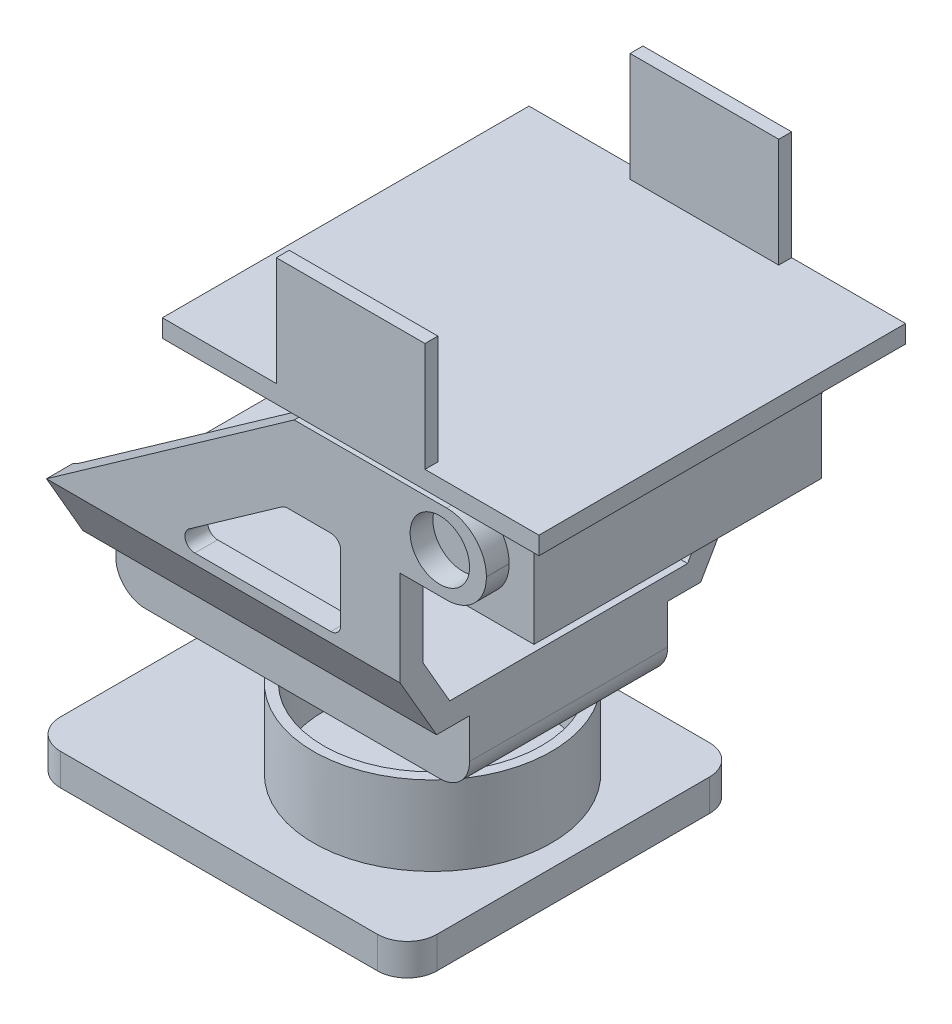
SolidWorks part; units mm, degrees
ref_plane "Alzado" through (0, 0, 0) normal (0, 0, 1) x (1, 0, 0)
ref_plane "Planta" through (0, 0, 0) normal (0, 1, 0) x (1, 0, 0)
ref_plane "Vista lateral" through (0, 0, 0) normal (1, 0, 0) x (0, 0, -1)
sketch "Croquis1" plane through (0, 0, 0) normal (0, 1, 0) x (1, 0, 0)
  line L1 (-16, -16.75) -> (16, -16.75)
  line L2 (-19, -13.75) -> (-19, 13.75)
  line L3 (-16, 16.75) -> (16, 16.75)
  line L4 (19, -13.75) -> (19, 13.75)
  line L5 (-19, -16.75) -> (19, 16.75) construction
  line L6 (-19, 16.75) -> (19, -16.75) construction
  arc A0 (-16, -16.75) -> (-19, -13.75) centre (-16, -13.75) cw
  arc A1 (16, -16.75) -> (19, -13.75) centre (16, -13.75) ccw
  arc A2 (16, 16.75) -> (19, 13.75) centre (16, 13.75) cw
  arc A3 (-19, 13.75) -> (-16, 16.75) centre (-16, 13.75) cw
  point P0 (0, 0)
  dimension "D3" = 3
  dimension "D1" = 38
  dimension "D2" = 33.5
extrude "Saliente-Extruir1" add sketch "Croquis1" along normal blind 3.2
sketch "Croquis2" plane through (0, 3.2, 0) normal (0, 1, 0) x (1, 0, 0)
  line L0 (4.8, 15.0241) -> (4.8, -18.394) construction
  line L1 (24.2913, 0) -> (-22.5361, 0) construction
  line L2 (19, -13.75) -> (19, 13.75) construction
  circle A0 centre (4.8, 0) radius 12
  circle A1 centre (4.8, 0) radius 11
  point P9 (0, 0)
  dimension "D2" = 24
  dimension "D1" = 14.2
  dimension "D3" = 1
extrude "Saliente-Extruir2" add sketch "Croquis2" along normal blind 8
sketch "Croquis3" plane through (0, 0, 0) normal (0, 0, 1) x (1, 0, 0)
  line L0 (4.8, 15.1383) -> (4.8, -3.1383) construction
  line L1 (16.8, 11.2) -> (-7.2, 11.2) construction
  line L2 (11.8, 13.2) -> (-10.42, 13.2)
  line L3 (11.8, 13.2) -> (11.8, 11.2)
  line L4 (11.8, 11.2) -> (-10.42, 11.2)
  line L5 (-10.42, 13.2) -> (-10.42, 11.2)
  dimension "D1" = 4.8
  dimension "D2" = 22.22
  dimension "D3" = 7
  dimension "D4" = 2
extrude "Saliente-Extruir3" add sketch "Croquis3" along normal mid plane 12
sketch "Croquis4" plane through (0, 0, 0) normal (0, 0, 1) x (1, 0, 0)
  line L0 (0.69, 13.2) -> (0.69, 23.3962) construction
  line L1 (11.8, 13.2) -> (-10.42, 13.2) construction
  line L3 (18.54, 20.2) -> (-17.16, 20.2)
  line L4 (18.54, 20.2) -> (18.54, 16.2)
  line L5 (15.54, 13.2) -> (-14.16, 13.2)
  line L6 (-17.16, 20.2) -> (-17.16, 16.2)
  arc A0 (18.54, 16.2) -> (15.54, 13.2) centre (15.54, 16.2) cw
  arc A1 (-17.16, 16.2) -> (-14.16, 13.2) centre (-14.16, 16.2) ccw
  point P8 (0.69, 23.3962)
  point P9 (-17.16, 21.2055)
  point P14 (-17.16, 13.2)
  dimension "D3" = 3
  dimension "D1" = 7
  dimension "D2" = 35.7
extrude "Saliente-Extruir4" add sketch "Croquis4" along normal mid plane 20
sketch "Croquis5" plane through (18.54, 0, 0) normal (1, 0, 0) x (0, 0, -1)
  line L0 (0, 29.5773) -> (0, 9.2688) construction
  line L1 (0, 22.5) -> (0, 20.2)
  line L2 (13.3279, 20.2) -> (-13.3279, 20.2)
  line L3 (-13.3279, 20.2) -> (-17, 26.5603)
  line L4 (-17, 26.5603) -> (-17, 44.2)
  line L5 (-17, 44.2) -> (-14.7, 44.2)
  line L6 (-14.7, 44.2) -> (-14.7, 27.1765)
  line L7 (-14.7, 27.1765) -> (-12, 22.5)
  line L8 (-12, 22.5) -> (12, 22.5)
  line L9 (-10, 20.2) -> (10, 20.2) construction
  line L10 (14.7, 27.1765) -> (12, 22.5)
  line L11 (14.7, 44.2) -> (14.7, 27.1765)
  line L12 (17, 44.2) -> (14.7, 44.2)
  line L13 (17, 26.5603) -> (17, 44.2)
  line L14 (13.3279, 20.2) -> (17, 26.5603)
  line M11 (10, 20.2) -> (-10, 20.2)
  dimension "D1" = 2.3
  dimension "D2" = 2.3
  dimension "D3" = 2.3
  dimension "D4" = 24
  dimension "D5" = 12
  dimension "D6" = 17
  dimension "D7" = 120
extrude "Saliente-Extruir5" add sketch "Croquis5" along direction (1, 0, 0) on the side against the normal up to vertex (35.7 mm away) contours L8 L7 L6 L5 L4 L3 L2 L1 M11 | L2 L14 L13 L12 L11 L10 L8 L1 M11
sketch "Croquis6" plane through (0, 0, 0) normal (0, 0, 1) x (1, 0, 0)
  line L0 (-17.16, 26.5603) -> (7.84, 44.2)
  line L1 (-17.16, 44.2) -> (18.54, 44.2) construction
  line L2 (7.84, 44.2) -> (-17.16, 44.2)
  line L3 (-17.16, 44.2) -> (-17.16, 26.5603)
  line L4 (-2.1838, 27.5603) -> (11.54, 27.5603)
  line L5 (12.54, 28.5603) -> (12.54, 35.1603)
  line L6 (6.5936, 35.9773) -> (-2.7603, 29.3773)
  line L7 (7.1701, 36.1603) -> (11.54, 36.1603)
  line L8 (-17.16, 26.5603) -> (18.54, 26.5603) construction
  line L9 (18.54, 26.5603) -> (18.54, 44.2) construction
  arc A0 (11.54, 27.5603) -> (12.54, 28.5603) centre (11.54, 28.5603) ccw
  arc A1 (-2.1838, 27.5603) -> (-2.7603, 29.3773) centre (-2.1838, 28.5603) cw
  arc A2 (7.1701, 36.1603) -> (6.5936, 35.9773) centre (7.1701, 35.1603) ccw
  arc A3 (11.54, 36.1603) -> (12.54, 35.1603) centre (11.54, 35.1603) cw
  point P17 (12.54, 27.5603)
  point P24 (12.54, 36.1603)
  dimension "D6" = 1
  dimension "D1" = 25
  dimension "D2" = 6
  dimension "D3" = 6
  dimension "D4" = 8.6
  dimension "D5" = 1
extrude "Cortar-Extruir1" cut sketch "Croquis6" against normal mid plane 90
sketch "Croquis7" plane through (0, 0, -17) normal (0, 0, -1) x (-1, 0, 0)
  line L0 (-7.1701, 36.1603) -> (-35.3255, 36.1603) construction
  line L1 (-7.84, 44.2) -> (-35.7356, 44.2) construction
  line L2 (-35.3255, 40.1801) -> (2.9042, 40.1801) construction
  line L3 (-18.54, 44.2) -> (-23.24, 44.2)
  line L4 (-18.54, 44.2) -> (-18.54, 36.1603)
  line L5 (-18.54, 36.1603) -> (-23.24, 36.1603)
  line L6 (-27.24, 40.2) -> (-27.24, 40.1603)
  line L7 (-25.54, 40.1801) -> (-25.54, 44.4282) construction
  line L8 (-27.24, 40.1801) -> (-27.24, 44.8707) construction
  arc A0 (-23.24, 36.1603) -> (-27.24, 40.1603) centre (-23.24, 40.1603) cw
  arc A1 (-23.24, 44.2) -> (-27.24, 40.2) centre (-23.24, 40.2) ccw
  circle A2 centre (-22.54, 40.1801) radius 3
  point P13 (-27.24, 36.1603)
  point P16 (-27.24, 44.2)
  dimension "D2" = 4
  dimension "D3" = 6
  dimension "D1" = 8.7
  dimension "D4" = 1.7
extrude "Saliente-Extruir6" add sketch "Croquis7" against normal blind 2.3
mirror "Simetría1" about plane through (0, 0, 0) normal (0, 0, 1) of "Saliente-Extruir6"
sketch "Croquis8" plane through (0, 0, 0) normal (0, 0, 1) x (1, 0, 0)
  line L0 (22.54, 40.1801) -> (-13.9654, 40.1801) construction
  line L1 (29.54, 34.1801) -> (6.54, 34.1801)
  line L2 (29.54, 34.1801) -> (29.54, 46.1801)
  line L3 (29.54, 46.1801) -> (6.54, 46.1801)
  line L4 (6.54, 34.1801) -> (6.54, 46.1801)
  line L5 (22.54, 46.1801) -> (22.54, 34.1801) construction
  point P9 (0, 0)
  point P10 (0, 0)
  point P11 (22.54, 40.1801)
  dimension "D1" = 23
  dimension "D2" = 7
  dimension "D3" = 12
extrude "Saliente-Extruir7" add sketch "Croquis8" along normal mid plane 29 separate body
sketch "Croquis9" plane through (0, 0, 0) normal (0, 0, 1) x (1, 0, 0)
  line L0 (29.54, 46.1801) -> (6.54, 46.1801) construction
  line L1 (-3.96, 47.9801) -> (34.04, 47.9801)
  line L2 (-3.96, 47.9801) -> (-3.96, 46.1801)
  line L3 (-3.96, 46.1801) -> (34.04, 46.1801)
  line L4 (34.04, 47.9801) -> (34.04, 46.1801)
  line L5 (29.54, 34.1801) -> (29.54, 46.1801) construction
  dimension "D1" = 1.8
  dimension "D2" = 38
  dimension "D3" = 4.5
extrude "Saliente-Extruir8" add sketch "Croquis9" along normal mid plane 37
sketch "Croquis10" plane through (0, 0, 18.5) normal (0, 0, 1) x (1, 0, 0)
  line L0 (15.04, 65.5219) -> (15.04, 39.9744) construction
  line L1 (34.04, 47.9801) -> (-3.96, 47.9801) construction
  line L2 (22.54, 47.9801) -> (7.54, 47.9801)
  line L3 (15.04, 47.9801) -> (15.04, 58.9801)
  line L4 (22.54, 58.9801) -> (7.54, 58.9801)
  line L5 (7.54, 47.9801) -> (7.54, 58.9801)
  line L7 (22.54, 47.9801) -> (22.54, 58.9801)
  point P10 (15.04, 65.5219)
  point P13 (-16.8491, 48.069)
  line M10 (34.04, 47.9801) -> (-3.96, 47.9801)
  dimension "D1" = 11
  dimension "D3" = 7.5
extrude "Saliente-Extruir9" add sketch "Croquis10" against normal blind 1.3 contours L5 L2 L3 L4 | L7 L4 L3 M10
mirror "Simetría2" about plane through (0, 0, 0) normal (0, 0, 1) of "Saliente-Extruir9"
